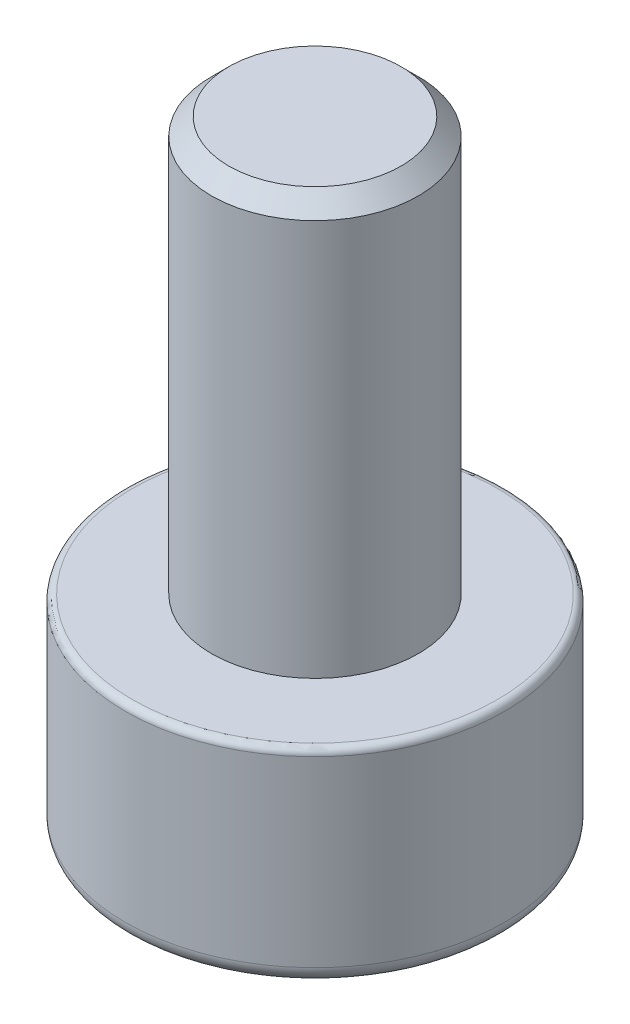
SolidWorks part; units mm, degrees
ref_plane "Front Plane" through (0, 0, 0) normal (0, 0, 1) x (1, 0, 0)
ref_plane "Top Plane" through (0, 0, 0) normal (0, 1, 0) x (1, 0, 0)
ref_plane "Right Plane" through (0, 0, 0) normal (1, 0, 0) x (0, 0, -1)
sketch "Sketch1" plane through (0, 0, 0) normal (0, 1, 0) x (1, 0, 0)
  circle A0 centre (0, 0) radius 2.75
  dimension "D1" = 5.5
extrude "Boss-Extrude1" add sketch "Sketch1" along normal blind 3
sketch "Sketch2" plane through (0, 3, 0) normal (0, 1, 0) x (1, 0, 0)
  circle A0 centre (0, 0) radius 1.5
  dimension "D1" = 3
extrude "Boss-Extrude2" add sketch "Sketch2" along normal blind 6 contours A0
sketch "Sketch3" plane through (0, 0, 0) normal (0, -1, 0) x (1, 0, 0)
  line L1 (0.9342, 0.9746) -> (-0.3769, 1.2963)
  line L2 (-0.3769, 1.2963) -> (-1.3111, 0.3217)
  line L3 (-1.3111, 0.3217) -> (-0.9342, -0.9746)
  line L4 (-0.9342, -0.9746) -> (0.3769, -1.2963)
  line L5 (0.3769, -1.2963) -> (1.3111, -0.3217)
  line L6 (1.3111, -0.3217) -> (0.9342, 0.9746)
  circle A0 centre (0, 0) radius 1.1691 construction
  dimension "D1" = 2.7
extrude "Cut-Extrude1" cut sketch "Sketch3" against normal blind 1.5
chamfer "Chamfer1" distance 0.25 distance2 0.25 6 edges at (-0.2786, 0, -1.1355) (-1.1226, 0, -0.3264) (-0.844, 0, 0.809) (0.2786, 0, 1.1355) (1.1226, 0, 0.3264) (0.844, 0, -0.809)
fillet "Fillet1" radius 0.25 1 edges at (0, 0, 2.75)
chamfer "Chamfer2" distance 0.25 angle 45 1 edges at (0, 9, 1.5)
fillet "Fillet2" radius 0.1 1 edges at (0, 3, 2.75)
